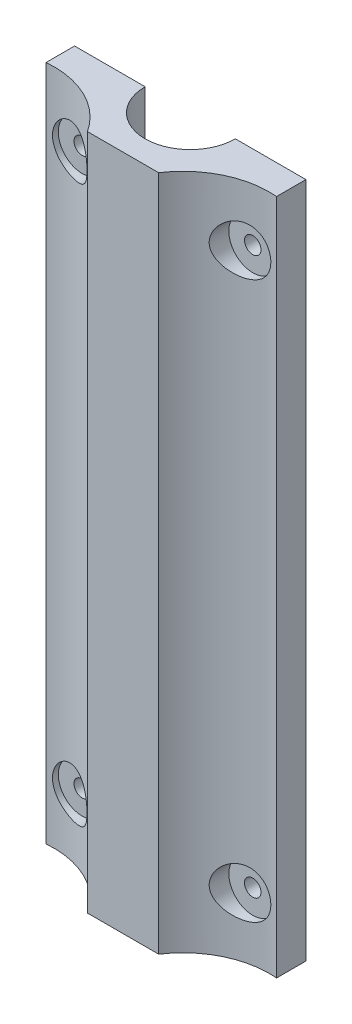
SolidWorks part; units mm, degrees
ref_plane "Ebene vorne" through (0, 0, 0) normal (0, 0, 1) x (1, 0, 0)
ref_plane "Ebene oben" through (0, 0, 0) normal (0, 1, 0) x (1, 0, 0)
ref_plane "Ebene rechts" through (0, 0, 0) normal (1, 0, 0) x (0, 0, -1)
sketch "Skizze3" plane through (0, 0, 0) normal (0, 0, 1) x (1, 0, 0)
  line L0 (0, 0) -> (-11, 0)
  line L1 (-11, 0) -> (-11, 90)
  line L2 (-11, 90) -> (-6, 90)
  line L3 (-6, 90) -> (-6, 10)
  line L4 (-6, 10) -> (0, 10)
  line L5 (0, 10) -> (0, 0)
  line L6 (0, 0) -> (0, 91.7062) construction
  dimension "D1" = 90
  dimension "D2" = 11
  dimension "D3" = 80
  dimension "D4" = 5
revolve "Rotation1" add sketch "Skizze3" angle 180 about L6
sketch "Skizze6" plane through (0, 90, 0) normal (0, 1, 0) x (1, 0, 0)
  line L0 (-9.3806, -5.7449) -> (-9.3806, 0)
  line L1 (-6, 0) -> (-11, 0) construction
  arc A0 (-11, 0) -> (11, 0) centre (0, 0) ccw construction
extrude "Schnitt-Linear austragen2" cut sketch "Skizze6" against normal blind 90 and the other way through all
sketch "Skizze7" plane through (0, 0, 0) normal (0, -1, 0) x (1, 0, 0)
  line L1 (9.3806, 5.7449) -> (9.3806, 0)
  line L2 (11, 0) -> (-9.3806, 0) construction
  arc A0 (11, 0) -> (-9.3806, 5.7449) centre (0, 0) ccw construction
extrude "Schnitt-Linear austragen3" cut sketch "Skizze7" against normal blind 90 and the other way through all
sketch "Skizze8" plane through (0, 90, 0) normal (0, 1, 0) x (1, 0, 0)
  line L1 (-9.3806, 0) -> (-19.3806, 0)
  line L2 (-9.3806, 0) -> (-9.3806, -5)
  line L3 (-9.3806, -5) -> (-19.3806, -5)
  line L4 (-19.3806, 0) -> (-19.3806, -5)
  dimension "D1" = 10
  dimension "D2" = 5
extrude "Aufsatz-Linear austragen2" add sketch "Skizze8" against normal blind 90
sketch "Skizze9" plane through (0, 90, 0) normal (0, 1, 0) x (1, 0, 0)
  line L1 (9.3806, 0) -> (19.3806, 0)
  line L2 (9.3806, 0) -> (9.3806, -5)
  line L3 (9.3806, -5) -> (19.3806, -5)
  line L4 (19.3806, 0) -> (19.3806, -5)
  dimension "D1" = 10
  dimension "D2" = 5
extrude "Aufsatz-Linear austragen3" add sketch "Skizze9" against normal blind 90
sketch "Skizze15" plane through (0, 0, 0) normal (0, 0, -1) x (-1, 0, 0)
  line L0 (0, 10) -> (0, 0) construction
  line L1 (6, 10) -> (-6, 10) construction
sketch "Skizze16" plane through (0, 0, 0) normal (0, -1, 0) x (1, 0, 0)
  circle A0 centre (0, 0) radius 1.1
  dimension "D1" = 2.2
extrude "Schnitt-Linear austragen8" cut sketch "Skizze16" against normal through all
sketch "Skizze18" plane through (0, 0, 0) normal (0, -1, 0) x (1, 0, 0)
  circle A0 centre (0, 0) radius 4
  dimension "D1" = 8
extrude "Schnitt-Linear austragen9" cut sketch "Skizze18" against normal blind 5
sketch "Skizze13" plane through (0, 0, 0) normal (0, -1, 0) x (1, 0, 0)
  circle A0 centre (0, 0) radius 4
  dimension "D1" = 8
sketch "Skizze20" plane through (0, 90, 0) normal (0, 1, 0) x (1, 0, 0)
  line L1 (10.4001, -11) -> (-11.3005, -11)
  line L2 (10.4001, -11) -> (10.4001, -9)
  line L3 (10.4001, -9) -> (-11.3005, -9)
  line L4 (-11.3005, -11) -> (-11.3005, -9)
  dimension "D1" = 2
extrude "Schnitt-Linear austragen10" cut sketch "Skizze20" against normal through all
ref_plane "Ebene1" through (-9.3806, 0, 5.7449) normal (0, -1, 0) x (-1, 0, 0)
sketch "Skizze22" plane through (0, 90, 0) normal (0, 1, 0) x (1, 0, 0)
  line L0 (-14.3806, -5) -> (-14.3806, -15.3568) construction
  line L1 (-19.3806, -5) -> (-9.3806, -5) construction
  line L2 (14.3806, -5) -> (14.3806, -15.3568) construction
  line L3 (9.3806, -5) -> (19.3806, -5) construction
  line L4 (-14.3806, -15.3568) -> (14.3806, -15.3568) construction
  circle A0 centre (-14.3806, -15.3568) radius 11.6085
  circle A1 centre (14.3806, -15.3568) radius 11.5006
extrude "Schnitt-Linear austragen17" cut sketch "Skizze22" against normal through all
sketch "Skizze24" plane through (0, 90, 0) normal (0, 1, 0) x (1, 0, 0)
  line L0 (6, 0) -> (19.3806, 0) construction
  line L1 (19.3806, -5) -> (15.3806, -5)
  line L2 (19.3806, -5) -> (19.3806, 0)
  line L3 (19.3806, 0) -> (15.3806, 0)
  line L4 (15.3806, -5) -> (15.3806, 0)
  line L6 (-19.3806, 0) -> (-15.3806, 0)
  line L7 (-19.3806, 0) -> (-19.3806, -5)
  line L8 (-19.3806, -5) -> (-15.3806, -5)
  line L9 (-15.3806, 0) -> (-15.3806, -5)
  dimension "D1" = 4
  dimension "D2" = 4
extrude "Schnitt-Linear austragen18" cut sketch "Skizze24" against normal through all
sketch3d "3D-Skizze1" plane through (0, 0, 0) normal (0, 0, 1) x (1, 0, 0)
ref_plane "Ebene2" through (-0.0143, 0, 3.8021) normal (0.0038, 0, -1) x (-1, 0, -0.0038)
ref_plane "Ebene4" through (-0.023, 0, 6.1342) normal (0.0038, 0, -1) x (-1, 0, -0.0038)
hole_wizard "Stirnsenkung für M2 Sechskantschraube, Gewinde bis Kopf10" positions "Skizze34" profile "Skizze35" counterbore size "M2" standard "ANSI Metrisch"
sketch "Skizze34" plane through (-0.023, 0, 6.1342) normal (0.0038, 0, -1) x (-1, 0, -0.0038)
  line L0 (15.3663, 90) -> (4.6335, 90) construction
  line L1 (15.3663, 90) -> (15.3663, 0) construction
  line L2 (-15.3951, 0) -> (-15.3951, 90) construction
  line L3 (-4.8303, 90) -> (-15.3951, 90) construction
  line L4 (4.6335, 0) -> (15.3663, 0) construction
  line L5 (-15.3951, 0) -> (-4.8303, 0) construction
  point P0 (11.3663, 82)
  point P2 (11.3663, 8)
  point P4 (-11.3951, 8)
  point P6 (-11.3951, 82)
  dimension "D1" = 8
  dimension "D2" = 4
  dimension "D3" = 4
  dimension "D4" = 8
  dimension "D5" = 4
  dimension "D6" = 8
  dimension "D7" = 8
  dimension "D8" = 4
sketch "Skizze35" plane through (-11.3892, 82, 6.0916) normal (0, 1, 0) x (1, 0, 0.0038)
  line L0 (0, 0) -> (0, 12.6609)
  line L1 (0, 12.6609) -> (1.1, 12)
  line L2 (1.1, 12) -> (1.1, 3.1)
  line L3 (1.1, 3.1) -> (3.19, 3.1)
  line L4 (3.19, 3.1) -> (3.19, 0)
  line L5 (3.19, 0) -> (0, 0)
  line L10 (0, 12.6609) -> (-1.1, 12) construction
  line L11 (0, -6.35) -> (0, 107.95) construction
  dimension "Bohrerdurchmesser" = 2.2
  dimension "Bohrungstiefe" = 12
  dimension "Senkdurchmesser2" = 6.38
  dimension "Senktiefe2" = 3.1
  dimension "Spitzenwinkel" = 118
